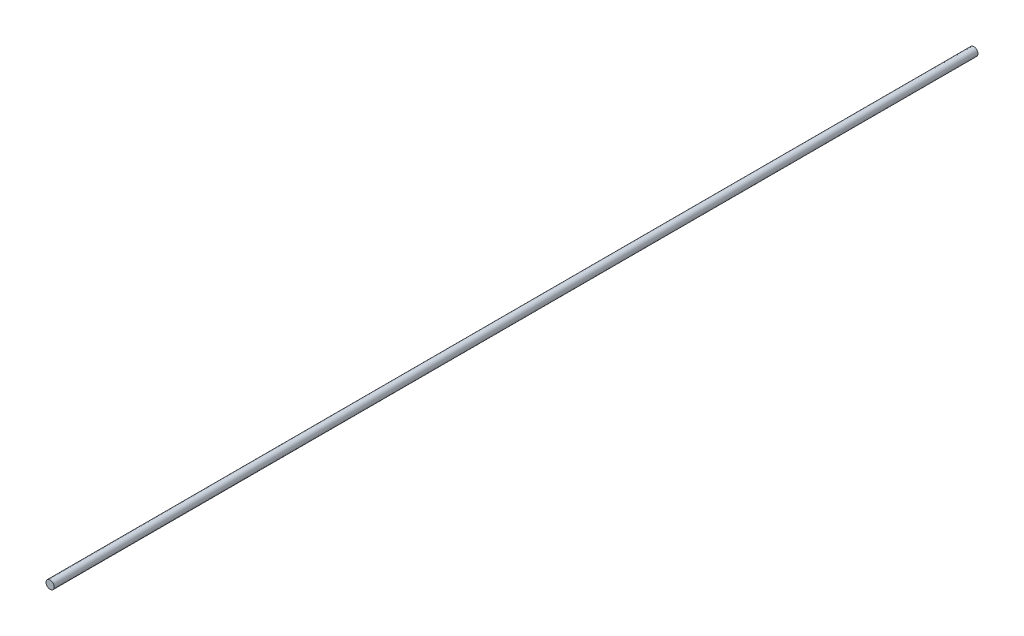
SolidWorks part; units mm, degrees
material "AISI 1020"
ref_plane "Front Plane" through (0, 0, 0) normal (0, 0, 1) x (1, 0, 0)
ref_plane "Top Plane" through (0, 0, 0) normal (0, 1, 0) x (1, 0, 0)
ref_plane "Right Plane" through (0, 0, 0) normal (1, 0, 0) x (0, 0, -1)
sketch "Sketch1" plane through (0, 0, 0) normal (0, 0, 1) x (1, 0, 0)
  circle A0 centre (0, 0) radius 4
  dimension "D1" = 8
extrude "Boss-Extrude1" add sketch "Sketch1" along normal blind 900
sketch "Sketch2" plane through (0, 0, 0) normal (0, 1, 0) x (1, 0, 0)
  line L0 (-2.7133, -93.4584) -> (2.6276, -93.4584)
  line L1 (-2.7133, -3.4584) -> (2.6276, -3.4584)
  line L2 (-2.7133, -3.4584) -> (-2.7133, -20.5302)
  line L3 (-2.7133, -20.5302) -> (2.6276, -20.5302)
  line L4 (2.6276, -3.4584) -> (2.6276, -20.5302)
  line L5 (-2.7133, -93.4584) -> (-2.7133, -110.5302)
  line L6 (-2.7133, -110.5302) -> (2.6276, -110.5302)
  line L7 (2.6276, -93.4584) -> (2.6276, -110.5302)
  line L8 (-2.7133, -183.4584) -> (2.6276, -183.4584)
  line L9 (-2.7133, -183.4584) -> (-2.7133, -200.5302)
  line L10 (-2.7133, -200.5302) -> (2.6276, -200.5302)
  line L11 (2.6276, -183.4584) -> (2.6276, -200.5302)
  line L12 (-2.7133, -273.4584) -> (2.6276, -273.4584)
  line L13 (-2.7133, -273.4584) -> (-2.7133, -290.5302)
  line L14 (-2.7133, -290.5302) -> (2.6276, -290.5302)
  line L15 (2.6276, -273.4584) -> (2.6276, -290.5302)
  line L16 (-2.7133, -363.4584) -> (2.6276, -363.4584)
  line L17 (-2.7133, -363.4584) -> (-2.7133, -380.5302)
  line L18 (-2.7133, -380.5302) -> (2.6276, -380.5302)
  line L19 (2.6276, -363.4584) -> (2.6276, -380.5302)
  line L20 (-2.7133, -453.4584) -> (2.6276, -453.4584)
  line L21 (-2.7133, -453.4584) -> (-2.7133, -470.5302)
  line L22 (-2.7133, -470.5302) -> (2.6276, -470.5302)
  line L23 (2.6276, -453.4584) -> (2.6276, -470.5302)
  line L24 (-2.7133, -543.4584) -> (2.6276, -543.4584)
  line L25 (-2.7133, -543.4584) -> (-2.7133, -560.5302)
  line L26 (-2.7133, -560.5302) -> (2.6276, -560.5302)
  line L27 (2.6276, -543.4584) -> (2.6276, -560.5302)
  line L28 (-2.7133, -633.4584) -> (2.6276, -633.4584)
  line L29 (-2.7133, -633.4584) -> (-2.7133, -650.5302)
  line L30 (-2.7133, -650.5302) -> (2.6276, -650.5302)
  line L31 (2.6276, -633.4584) -> (2.6276, -650.5302)
  line L32 (-2.7133, -723.4584) -> (2.6276, -723.4584)
  line L33 (-2.7133, -723.4584) -> (-2.7133, -740.5302)
  line L34 (-2.7133, -740.5302) -> (2.6276, -740.5302)
  line L35 (2.6276, -723.4584) -> (2.6276, -740.5302)
  line L36 (-2.7133, -813.4584) -> (2.6276, -813.4584)
  line L37 (-2.7133, -813.4584) -> (-2.7133, -830.5302)
  line L38 (-2.7133, -830.5302) -> (2.6276, -830.5302)
  line L39 (2.6276, -813.4584) -> (2.6276, -830.5302)
  dimension "D1" = 10
extrude "Cut-Extrude1" cut sketch "Sketch2" against normal blind 10 from offset 3.5
